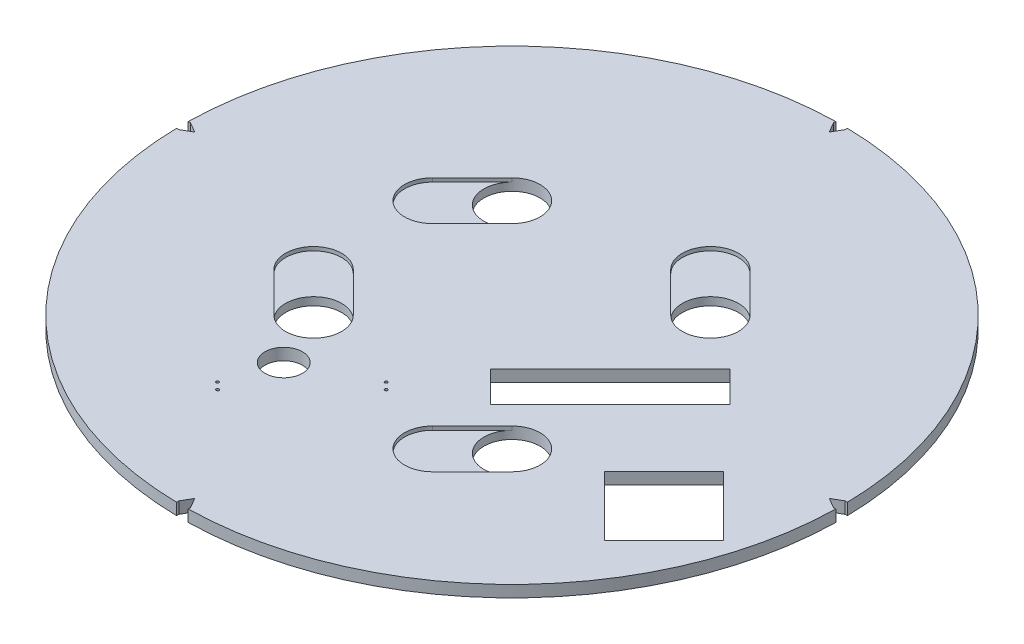
SolidWorks part; units mm, degrees
ref_plane "前视基准面" through (0, 0, 0) normal (0, 0, 1) x (1, 0, 0)
ref_plane "上视基准面" through (0, 0, 0) normal (0, 1, 0) x (1, 0, 0)
ref_plane "右视基准面" through (0, 0, 0) normal (1, 0, 0) x (0, 0, -1)
sketch "草图1" plane through (0, 0, 0) normal (0, 1, 0) x (1, 0, 0)
  circle A0 centre (0, 0) radius 705
  dimension "D1" = 1410
extrude "凸台-拉伸1" add sketch "草图1" along normal blind 25
sketch "草图2" plane through (0, 25, 0) normal (0, 1, 0) x (1, 0, 0)
  line L0 (-12.5, -699.9942) -> (-12.5, -1517.4112) construction
  line L1 (0, -678.3436) -> (-12.5, -699.9942) construction
  line L2 (12.5, -699.9942) -> (0, -678.3436) construction
  line L3 (12.5, -699.9942) -> (12.5, -1517.4112) construction
  line L4 (-12.5, -699.9942) -> (-12.5, -704.8892)
  line L5 (0, -678.3436) -> (-12.5, -699.9942)
  line L6 (12.5, -699.9942) -> (0, -678.3436)
  line L7 (12.5, -699.9942) -> (12.5, -704.8892)
  arc A0 (12.5, -704.8892) -> (-12.5, -704.8892) centre (0, 0) cw
  dimension "D1" = 705
extrude "切除-拉伸1" cut sketch "草图2" against normal up to next
pattern_circular "阵列(圆周)1" count 4 over 360 about axis through (0, 0, 0) along (0, 1, 0) of "切除-拉伸1"
sketch "草图7" plane through (0, 25, 0) normal (0, 1, 0) x (1, 0, 0)
  line L0 (0, 695) -> (0, -695) construction
  line L1 (326.2868, -609.1295) -> (206.0786, -488.9214)
  line L2 (326.2868, -609.1295) -> (467.7082, -467.7082)
  line L3 (467.7082, -467.7082) -> (347.5, -347.5)
  line L4 (206.0786, -488.9214) -> (347.5, -347.5)
  line L5 (326.2868, -609.1295) -> (347.5, -347.5) construction
  line L6 (467.7082, -467.7082) -> (206.0786, -488.9214) construction
  line L7 (-695, 0) -> (695, 0) construction
  line L8 (695, 0) -> (0, -695) construction
  line L9 (491.4392, -491.4392) -> (-491.4392, 491.4392) construction
  line L10 (-612.9008, -323.662) -> (-492.6926, -203.4538)
  line L11 (-612.9008, -323.662) -> (-471.4794, -465.0833)
  line L12 (-471.4794, -465.0833) -> (-351.2713, -344.8752)
  line L13 (-492.6926, -203.4538) -> (-351.2713, -344.8752)
  line L14 (-612.9008, -323.662) -> (-351.2713, -344.8752) construction
  line L15 (-471.4794, -465.0833) -> (-492.6926, -203.4538) construction
  line L16 (-332.2351, 613.6048) -> (-212.027, 493.3967)
  line L17 (-332.2351, 613.6048) -> (-473.6565, 472.1835)
  line L18 (-473.6565, 472.1835) -> (-353.4483, 351.9753)
  line L19 (-212.027, 493.3967) -> (-353.4483, 351.9753)
  line L20 (-332.2351, 613.6048) -> (-353.4483, 351.9753) construction
  line L21 (-473.6565, 472.1835) -> (-212.027, 493.3967) construction
  line L22 (605.0317, 332.9392) -> (484.8235, 212.731)
  line L23 (605.0317, 332.9392) -> (463.6103, 474.3606)
  line L24 (463.6103, 474.3606) -> (343.4022, 354.1524)
  line L25 (484.8235, 212.731) -> (343.4022, 354.1524)
  line L26 (605.0317, 332.9392) -> (343.4022, 354.1524) construction
  line L27 (463.6103, 474.3606) -> (484.8235, 212.731) construction
  line L28 (347.5, -347.5) -> (347.5, 0) construction
  circle A0 centre (0, 0) radius 695
  arc A1 (467.7082, -467.7082) -> (347.5, -347.5) centre (407.6041, -407.6041) ccw
  arc A2 (-471.4794, -465.0833) -> (-351.2713, -344.8752) centre (-411.3753, -404.9792) ccw
  arc A3 (-473.6565, 472.1835) -> (-353.4483, 351.9753) centre (-413.5524, 412.0794) ccw
  arc A4 (463.6103, 474.3606) -> (343.4022, 354.1524) centre (403.5062, 414.2565) ccw
  point P2 (336.8934, -478.3148)
  point P14 (-482.086, -334.2686)
  point P20 (-342.8417, 482.7901)
  point P26 (474.2169, 343.5458)
  point P35 (20.5792, -31.4481)
  dimension "D1" = 1390
  dimension "D2" = 200
  dimension "D3" = 170
sketch "草图8" plane through (0, 25, 0) normal (0, 1, 0) x (1, 0, 0)
  line L0 (491.4392, -491.4392) -> (-491.4392, 491.4392) construction
  circle A0 centre (247.4874, -247.4874) radius 60
  circle A4 centre (-212.132, -212.132) radius 60
  circle A5 centre (-212.132, 212.132) radius 60
  circle A6 centre (212.132, 212.132) radius 60
  circle A7 centre (212.132, -212.132) radius 60 [skipped]
  point P13 (0, 0)
  point P18 (0, 0)
  dimension "D3" = 120
  dimension "D1" = 120
  dimension "D2" = 350
  dimension "D4" = 300
  dimension "D5" = 4
extrude "切除-拉伸2" cut sketch "草图8" against normal up to next
sketch "草图9" plane through (0, 25, 0) normal (0, 1, 0) x (1, 0, 0)
  line L0 (0, 0) -> (388.546, -190.5149) construction
  line L1 (-695, 0) -> (695, 0) construction
  line L2 (388.546, -190.5149) -> (515.826, -190.5149) construction
  line L3 (515.826, 31.9108) -> (515.826, -334.5521) construction
  line L4 (388.546, -190.5149) -> (515.826, -63.2365)
  line L5 (388.546, -190.5149) -> (515.826, -317.7934)
  line L6 (643.106, -190.5149) -> (515.826, -317.7934)
  line L7 (643.106, -190.5149) -> (515.826, -63.2365)
  dimension "D1" = 26.12
  dimension "D2" = 432.74
  dimension "D3" = 127.28
  dimension "D4" = 180
  dimension "D5" = 180
extrude "切除-拉伸3" cut sketch "草图9" against normal through all
sketch "草图13" plane through (0, 0, 0) normal (0, -1, 0) x (1, 0, 0)
  line L1 (491.4392, 491.4392) -> (-491.4392, -491.4392) construction
  line L5 (165.0393, 165.0393) -> (398.0933, -68.0146)
  line L7 (398.0933, -68.0146) -> (332.5978, -133.5101)
  line L8 (99.5438, 99.5438) -> (332.5978, -133.5101)
  line L9 (165.0393, 165.0393) -> (99.5438, 99.5438)
extrude "切除-拉伸7" cut sketch "草图13" against normal through all
sketch "草图14" plane through (0, 0, 0) normal (0, -1, 0) x (1, 0, 0)
  line L0 (165.0393, 165.0393) -> (99.5438, 99.5438)
  line L1 (165.0393, 165.0393) -> (141.9974, 188.0813)
  line L2 (99.5438, 99.5438) -> (76.5019, 122.5858)
  line L3 (141.9974, 188.0813) -> (76.5019, 122.5858)
  line L4 (491.4392, 491.4392) -> (-491.4392, -491.4392) construction
  line L5 (398.0933, -68.0146) -> (165.0393, 165.0393) construction
  dimension "D1" = 32.5862
extrude "切除-拉伸8" cut sketch "草图14" against normal through all
sketch "草图18" plane through (0, 25, 0) normal (0, 1, 0) x (1, 0, 0)
  circle A0 centre (-156.5442, -331.6677) radius 40 construction
  circle A1 centre (-156.5442, -331.6677) radius 40
extrude "切除-拉伸13" cut sketch "草图18" against normal through all
sketch "草图19" plane through (0, 0, 0) normal (0, -1, 0) x (1, 0, 0)
  line L0 (-156.5442, 331.6677) -> (-113.3076, 374.9042) construction
  line L1 (-113.3076, 374.9042) -> (-3.7061, 265.3026) construction
  line L2 (-113.3076, 374.9042) -> (-184.0183, 445.6149) construction
  line L3 (-3.7061, 265.3026) -> (-10.7771, 258.2316) construction
  line L4 (-184.0183, 445.6149) -> (-191.0894, 438.5438) construction
  circle A0 centre (-10.7771, 258.2316) radius 3
  circle A1 centre (-191.0894, 438.5438) radius 3
  circle A2 centre (3.365, 272.3737) radius 3
  circle A3 centre (-176.9472, 452.6859) radius 3
extrude "切除-拉伸14" cut sketch "草图19" against normal blind 100
sketch "草图20" plane through (0, 25, 0) normal (0, 1, 0) x (1, 0, 0)
  line L0 (212.132, 212.132) -> (127.2792, 296.9848) construction
  line L2 (-84.8528, 84.8528) -> (-33625.8725, 33625.8725) construction
  line L4 (0, 0) -> (33541.0197, 33541.0197) construction
  line L5 (169.7056, 169.7056) -> (84.8528, 254.5584)
  line L6 (254.5584, 254.5584) -> (169.7056, 339.4113)
  line L7 (-212.132, -212.132) -> (-296.9848, -127.2792) construction
  line L8 (-169.7056, -169.7056) -> (-254.5584, -84.8528)
  line L9 (-254.5584, -254.5584) -> (-339.4113, -169.7056)
  line L10 (-212.132, 212.132) -> (-296.9848, 127.2792) construction
  line L11 (-169.7056, 169.7056) -> (-254.5584, 84.8528)
  line L12 (-254.5584, 254.5584) -> (-339.4113, 169.7056)
  line L13 (247.4874, -247.4874) -> (162.6346, -332.3402) construction
  line L14 (289.9138, -289.9138) -> (205.061, -374.7666)
  line L15 (205.061, -205.061) -> (120.2082, -289.9138)
  arc A0 (169.7056, 169.7056) -> (254.5584, 254.5584) centre (212.132, 212.132) ccw
  arc A1 (169.7056, 339.4113) -> (84.8528, 254.5584) centre (127.2792, 296.9848) ccw
  arc A3 (-169.7056, -169.7056) -> (-254.5584, -254.5584) centre (-212.132, -212.132) cw
  arc A4 (-339.4113, -169.7056) -> (-254.5584, -84.8528) centre (-296.9848, -127.2792) cw
  arc A5 (-169.7056, 169.7056) -> (-254.5584, 254.5584) centre (-212.132, 212.132) ccw
  arc A6 (-339.4113, 169.7056) -> (-254.5584, 84.8528) centre (-296.9848, 127.2792) ccw
  circle A7 centre (-212.132, 212.132) radius 60 construction
  arc A8 (289.9138, -289.9138) -> (205.061, -205.061) centre (247.4874, -247.4874) ccw
  arc A9 (120.2082, -289.9138) -> (205.061, -374.7666) centre (162.6346, -332.3402) ccw
  point P7 (169.7056, 254.5584)
  point P13 (-254.5584, 169.7056)
  point P16 (-254.5584, -169.7056)
  point P27 (205.061, -289.9138)
  dimension "D1" = 60
  dimension "D3" = 60
  dimension "D5" = 60
  dimension "D2" = 120
  dimension "D4" = 120
  dimension "D6" = 120
extrude "切除-拉伸15" cut sketch "草图20" against normal blind 8
